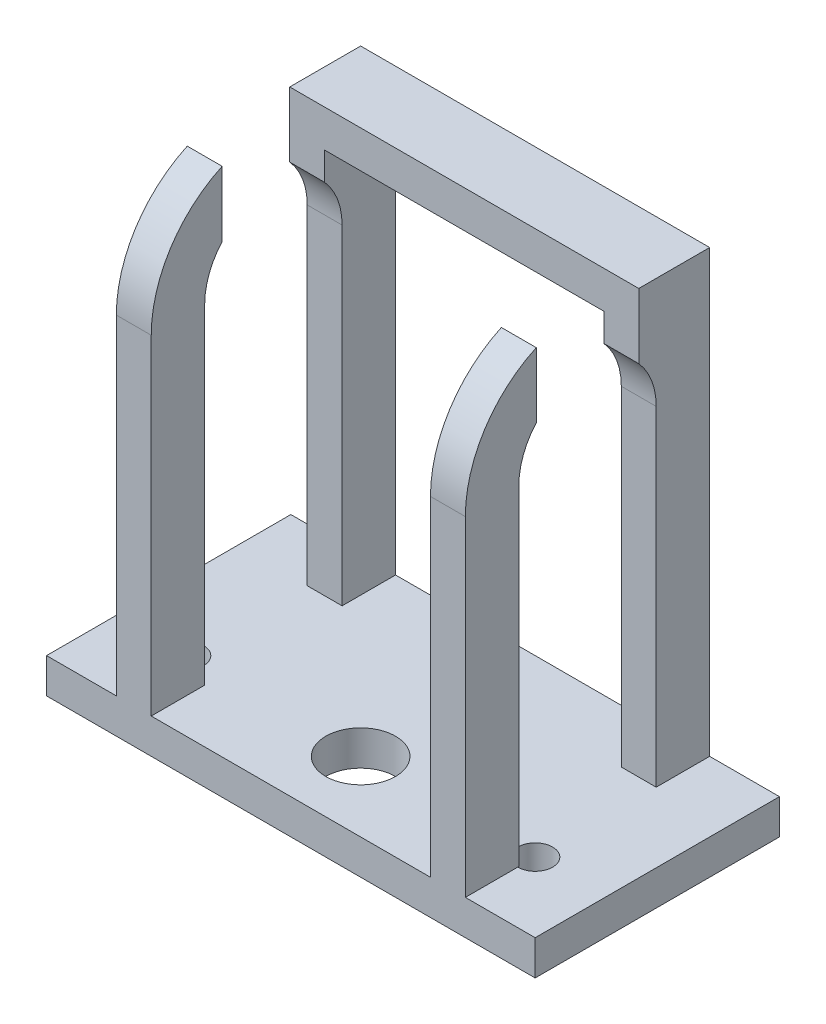
SolidWorks part; units mm, degrees
ref_plane "Front Plane" through (0, 0, 0) normal (0, 0, 1) x (1, 0, 0)
ref_plane "Top Plane" through (0, 0, 0) normal (0, 1, 0) x (1, 0, 0)
ref_plane "Right Plane" through (0, 0, 0) normal (1, 0, 0) x (0, 0, -1)
sketch "Sketch2" plane through (0, 0, 0) normal (0, 1, 0) x (1, 0, 0)
  line L0 (0, 31.75) -> (0, -12.7) construction
  line L1 (-44.45, -12.7) -> (44.45, -12.7)
  line L2 (-44.45, -12.7) -> (-44.45, 31.75)
  line L3 (-44.45, 31.75) -> (44.45, 31.75)
  line L4 (44.45, -12.7) -> (44.45, 31.75)
  circle A0 centre (0, 0) radius 6.35
  circle A1 centre (-31.75, 0) radius 3.175
  circle A2 centre (31.75, 0) radius 3.175
  point P0 (0, 0)
  point P14 (0, 0)
  point P15 (44.4693, 19.3102)
  dimension "D4" = 6.35
  dimension "D5" = 12.7
  dimension "D1" = 88.9
  dimension "D2" = 44.45
  dimension "D3" = 63.5
  dimension "D6" = 12.7
extrude "Boss-Extrude1" add sketch "Sketch2" along normal blind 6.35
ref_plane "Plane1" through (25.4, 0, 0) normal (1, 0, 0) x (0, 0, -1)
sketch "Sketch3" plane through (25.4, 0, 0) normal (1, 0, 0) x (0, 0, -1)
  line L0 (31.75, 6.35) -> (31.75, 0) construction
  line L1 (-12.7, 6.35) -> (31.75, 6.35)
  line L2 (-12.7, 6.35) -> (-12.7, 66.35)
  line L3 (-12.7, 66.35) -> (31.75, 66.35)
  line L4 (31.75, 6.35) -> (31.75, 66.35)
  circle A0 centre (9.525, 66.35) radius 22.225
  dimension "D1" = 60
extrude "Boss-Extrude2" add sketch "Sketch3" along normal blind 6.35 contours L2 L1 L4 L3 | A0
sketch "Sketch4" plane through (31.75, 0, 0) normal (1, 0, 0) x (0, 0, -1)
  line L0 (-12.7, 6.35) -> (-3.175, 6.35) construction
  line L1 (-2.975, 66.35) -> (22.025, 66.35)
  line L2 (-2.975, 66.35) -> (-2.975, 6.35)
  line L3 (-2.975, 6.35) -> (22.025, 6.35)
  line L4 (22.025, 66.35) -> (22.025, 6.35)
  line L6 (0.2, 74.6743) -> (18.85, 74.6743)
  line L7 (0.2, 74.6743) -> (0.2, 88.575)
  line L8 (0.2, 88.575) -> (18.85, 88.575)
  line L9 (18.85, 74.6743) -> (18.85, 88.575)
  circle A0 centre (9.525, 66.35) radius 12.5
  arc A1 (31.75, 66.35) -> (-12.7, 66.35) centre (9.525, 66.35) ccw construction
  point P15 (0, 0)
  dimension "D1" = 25
  dimension "D2" = 3.175
extrude "Cut-Extrude1" cut sketch "Sketch4" against normal up to surface (6.35 mm away) contours L2 L1 L4 L3 | A0 | L7 L6 L9 L8 up to face at (25.4, 41.9062, -9.525)
sketch "Sketch5" plane through (31.75, 0, 0) normal (1, 0, 0) x (0, 0, -1)
  line L0 (31.75, 6.35) -> (31.75, 66.35) construction
  line L1 (18.85, 86.5241) -> (31.75, 86.5241)
  line L2 (18.85, 86.5241) -> (18.85, 74.6743)
  line L3 (18.85, 74.6743) -> (31.75, 74.6743)
  line L4 (31.75, 86.5241) -> (31.75, 74.6743)
  line L5 (22.025, 66.35) -> (22.025, 6.35) construction
  line L6 (31.75, 74.6743) -> (22.025, 74.6743)
  line L7 (31.75, 74.6743) -> (31.75, 66.35)
  line L8 (31.75, 66.35) -> (22.025, 66.35)
  line L9 (22.025, 74.6743) -> (22.025, 66.35)
  point P13 (0, 0)
extrude "Boss-Extrude3" add sketch "Sketch5" against normal up to surface (6.35 mm away) contours L2 L1 L4 L3 | L7 L6 L9 L8 up to face at (25.4, 51.4628, -24.8277)
mirror "Mirror1" about plane through (0, 0, 0) normal (1, 0, 0) of "Boss-Extrude3", "Cut-Extrude1", "Boss-Extrude2"
sketch "Sketch6" plane through (31.75, 0, 0) normal (1, 0, 0) x (0, 0, -1)
  line L0 (31.75, 6.35) -> (31.75, 86.5241) construction
  line L1 (18.85, 86.5241) -> (31.75, 86.5241)
  line L2 (18.85, 86.5241) -> (18.85, 79.7543)
  line L3 (18.85, 79.7543) -> (31.75, 79.7543)
  line L4 (31.75, 86.5241) -> (31.75, 79.7543)
  dimension "D1" = 5.08
extrude "Boss-Extrude4" add sketch "Sketch6" against normal up to surface (57.15 mm away) up to face at (-25.4, 54.5108, -24.3361)
